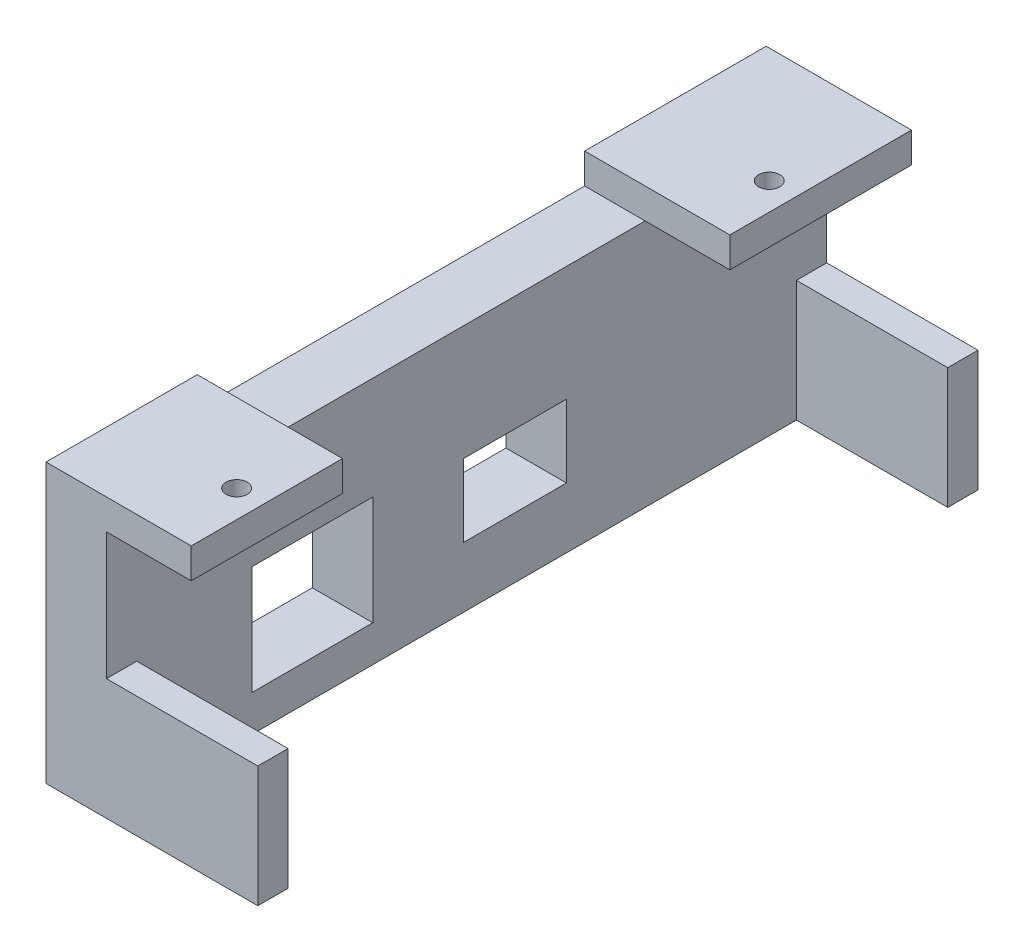
SolidWorks part; units mm, degrees
ref_plane "Ebene vorne" through (0, 0, 0) normal (0, 0, 1) x (1, 0, 0)
ref_plane "Ebene oben" through (0, 0, 0) normal (0, 1, 0) x (1, 0, 0)
ref_plane "Ebene rechts" through (0, 0, 0) normal (1, 0, 0) x (0, 0, -1)
sketch "Sketch1" plane through (0, 0, 0) normal (0, 1, 0) x (1, 0, 0)
  line L1 (-5, -59.5) -> (5, -59.5)
  line L2 (-5, -59.5) -> (-5, 59.5)
  line L3 (-5, 59.5) -> (5, 59.5)
  line L4 (5, -59.5) -> (5, 59.5)
  line L5 (-5, -59.5) -> (5, 59.5) construction
  line L6 (-5, 59.5) -> (5, -59.5) construction
  point P0 (0, 0)
  dimension "D1" = 10
  dimension "D2" = 119
extrude "Extrude1" add sketch "Sketch1" along normal blind 46
sketch "Sketch2" plane through (-5, 0, 0) normal (-1, 0, 0) x (0, 0, 1)
  line L0 (59.5, 46) -> (59.5, 0) construction
  line L5 (-59.5, 0) -> (-54.5, 0)
  line L6 (-59.5, 0) -> (-59.5, 20)
  line L7 (-59.5, 20) -> (-54.5, 20)
  line L8 (-54.5, 0) -> (-54.5, 20)
  line L9 (59.5, 0) -> (54.5, 0)
  line L10 (59.5, 0) -> (59.5, 20)
  line L11 (59.5, 20) -> (54.5, 20)
  line L12 (54.5, 0) -> (54.5, 20)
  line L13 (-59.5, 0) -> (59.5, 0) construction
  dimension "D1" = 20
  dimension "D2" = 5
  dimension "D3" = 5
extrude "Extrude2" add sketch "Sketch2" against normal blind 35
sketch "Sketch3" plane through (-5, 0, 0) normal (-1, 0, 0) x (0, 0, 1)
  line L0 (54.5, 20) -> (54.5, 0) construction
  line L1 (-59.5, 46) -> (-29.5, 46)
  line L2 (-59.5, 46) -> (-59.5, 41)
  line L3 (-59.5, 41) -> (-29.5, 41)
  line L4 (-29.5, 46) -> (-29.5, 41)
  line L5 (59.5, 46) -> (34.5, 46)
  line L6 (59.5, 46) -> (59.5, 41)
  line L7 (59.5, 41) -> (34.5, 41)
  line L8 (34.5, 46) -> (34.5, 41)
  line L9 (-16.5, 22) -> (0.5, 22)
  line L10 (-16.5, 22) -> (-16.5, 10)
  line L11 (-16.5, 10) -> (0.5, 10)
  line L12 (0.5, 22) -> (0.5, 10)
  line L13 (15.5, 24) -> (35.5, 24)
  line L14 (15.5, 24) -> (15.5, 6)
  line L15 (15.5, 6) -> (35.5, 6)
  line L16 (35.5, 24) -> (35.5, 6)
  line L17 (-29.5, 46) -> (34.5, 46)
  line L18 (-29.5, 46) -> (-29.5, 41)
  line L19 (-29.5, 41) -> (34.5, 41)
  line L20 (34.5, 46) -> (34.5, 41)
  line L21 (-59.5, 0) -> (59.5, 0) construction
  line L22 (-59.5, 46) -> (-59.5, 0) construction
  line M14 (59.5, 46) -> (-59.5, 46)
  dimension "D1" = 5
  dimension "D2" = 5
  dimension "D3" = 30
  dimension "D4" = 25
  dimension "D5" = 20
  dimension "D6" = 18
  dimension "D7" = 19
  dimension "D8" = 6
  dimension "D9" = 17
  dimension "D10" = 12
  dimension "D11" = 43
  dimension "D12" = 10
extrude "Extrude3" cut sketch "Sketch3" against normal blind 30 contours L4 L19 L8 M14 | L12 L9 L10 L11 | L16 L13 L14 L15
sketch "Sketch4" plane through (5, 0, 0) normal (1, 0, 0) x (0, 0, -1)
  line L1 (-59.5, 46) -> (-34.5, 46)
  line L2 (-59.5, 46) -> (-59.5, 41)
  line L3 (-59.5, 41) -> (-34.5, 41)
  line L4 (-34.5, 46) -> (-34.5, 41)
  line L5 (29.5, 41) -> (59.5, 41)
  line L6 (29.5, 41) -> (29.5, 46)
  line L7 (29.5, 46) -> (59.5, 46)
  line L8 (59.5, 41) -> (59.5, 46)
extrude "Extrude4" add sketch "Sketch4" along normal blind 14
sketch "Sketch5" plane through (0, 46, 0) normal (0, 1, 0) x (1, 0, 0)
  line L1 (5, 29.5) -> (5, -34.5) construction
  line L5 (30, -54.5) -> (5, -54.5) construction
  circle A0 centre (14.5, -47.5) radius 1.75
  circle A1 centre (14.5, 40.5) radius 1.75
  point P4 (0, 0)
  point P7 (13.2951, 44.8297)
  point P9 (0, 0)
  dimension "D1" = 3.5
  dimension "D2" = 3.5
  dimension "D3" = 7
  dimension "D4" = 14
  dimension "D5" = 9.5
  dimension "D6" = 9.5
extrude "Extrude5" cut sketch "Sketch5" against normal blind 5
sketch "Sketch7" plane through (0, 0, 0) normal (0, -1, 0) x (1, 0, 0)
  circle A0 centre (0, 45) radius 2
  circle A1 centre (0, -45) radius 2
  point P4 (0, 0)
  dimension "D1" = 4
  dimension "D2" = 4
  dimension "D3" = 45
  dimension "D4" = 45
extrude "Extrude6" cut sketch "Sketch7" against normal blind 10
